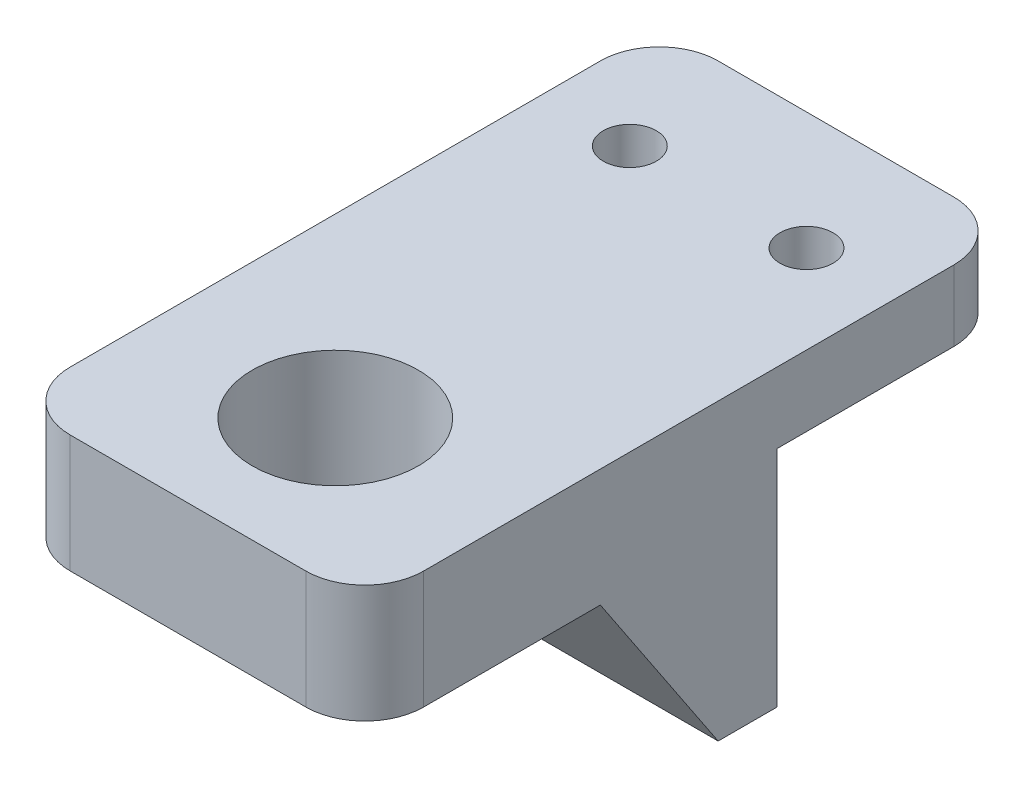
SolidWorks part; units mm, degrees
ref_plane "Front Plane" through (0, 0, 0) normal (0, 0, 1) x (1, 0, 0)
ref_plane "Top Plane" through (0, 0, 0) normal (0, 1, 0) x (1, 0, 0)
ref_plane "Right Plane" through (0, 0, 0) normal (1, 0, 0) x (0, 0, -1)
sketch "Sketch1" plane through (0, 0, 0) normal (0, 1, 0) x (1, 0, 0)
  line L0 (0, 43.035) -> (0, -16.7675) construction
  line L1 (-20.0245, 0) -> (20.6679, 0) construction
  line L2 (15, 42.5) -> (-15, 42.5)
  line L3 (-15, 42.5) -> (-15, -12.5)
  line L4 (-15, -12.5) -> (15, -12.5)
  line L5 (15, 42.5) -> (15, -12.5)
  circle A0 centre (0, 0) radius 2.6 construction
  circle A1 centre (-7.5, 32.5) radius 2.25
  circle A2 centre (7.5, 32.5) radius 2.25
  point P16 (0, -12.5)
  point P17 (0, 42.5)
  dimension "D1" = 5.2
  dimension "D2" = 4.5
  dimension "D3" = 7.5
  dimension "D4" = 32.5
  dimension "D5" = 15
  dimension "D6" = 55
  dimension "D7" = 10
extrude "Boss-Extrude1" add sketch "Sketch1" along normal blind 6
sketch "Sketch3" plane through (0, 0, 0) normal (0, -1, 0) x (1, 0, 0)
  line L0 (-15, 12.5) -> (15, 12.5)
  line L1 (15, 12.5) -> (15, -22.5)
  line L2 (15, -42.5) -> (15, 12.5) construction
  line L3 (15, -22.5) -> (-15, -22.5)
  line L4 (-15, -42.5) -> (-15, 12.5) construction
  line L5 (-15, -22.5) -> (-15, 12.5)
  dimension "D1" = 35
extrude "Boss-Extrude2" add sketch "Sketch3" along normal blind 4
sketch "Sketch4" plane through (-15, 0, 0) normal (-1, 0, 0) x (0, 0, 1)
  line L0 (-22.5, -4) -> (-22.5, -19)
  line L1 (-22.5, -19) -> (-17.5, -19)
  line L2 (-17.5, -19) -> (-7.5, -4)
  line L3 (12.5, -4) -> (-22.5, -4) construction
  line L4 (-7.5, -4) -> (-22.5, -4)
  dimension "D1" = 15
  dimension "D2" = 5
  dimension "D3" = 15
extrude "Boss-Extrude3" add sketch "Sketch4" against normal up to surface (30 mm away) up to face at (15, 0.6667, -17.5)
sketch "Sketch2" plane through (0, 6, 0) normal (0, 1, 0) x (1, 0, 0)
  circle A0 centre (0, 0) radius 7.05
  dimension "D1" = 14.1
extrude "Cut-Extrude1" cut sketch "Sketch2" against normal through all both and the other way through all
fillet "Fillet1" radius 5 4 edges at (15, 3, -42.5) (-15, 3, -42.5) (15, 1, 12.5) (-15, 1, 12.5)
